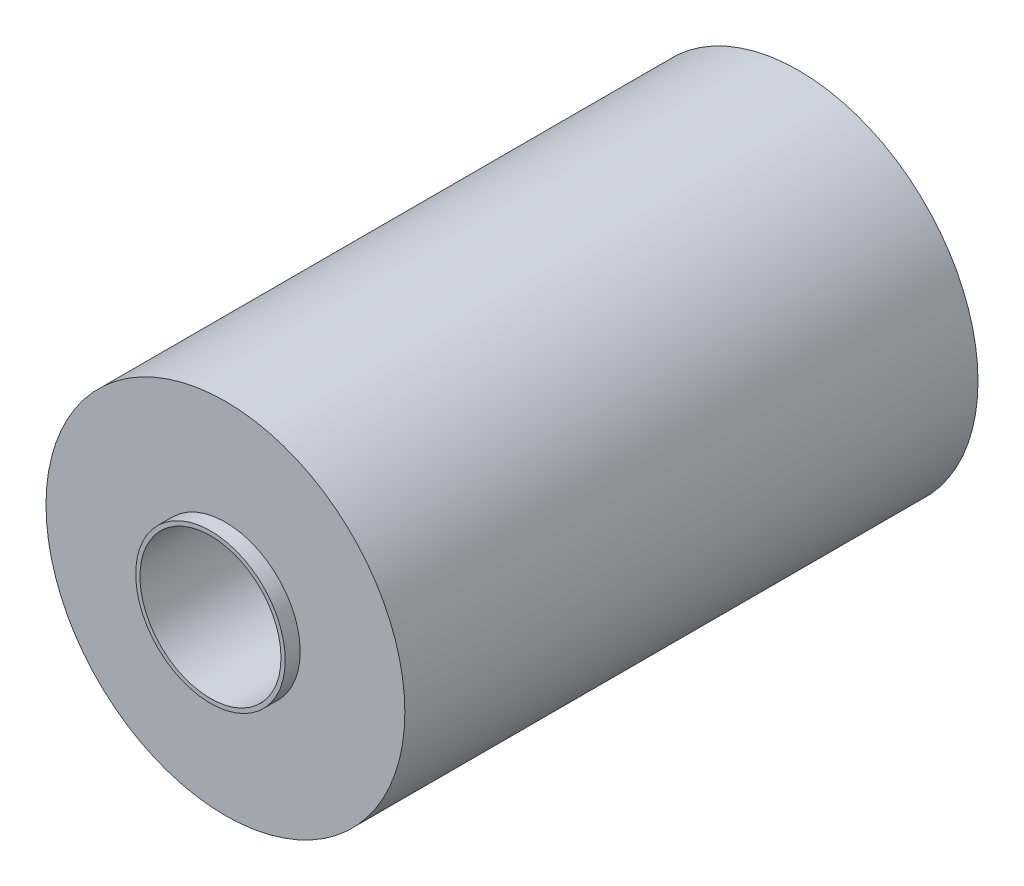
SolidWorks part; units mm, degrees
material "铜"
ref_plane "前视基准面" through (0, 0, 0) normal (0, 0, 1) x (1, 0, 0)
ref_plane "上视基准面" through (0, 0, 0) normal (0, 1, 0) x (1, 0, 0)
ref_plane "右视基准面" through (0, 0, 0) normal (1, 0, 0) x (0, 0, -1)
sketch "草图1" plane through (0, 0, 0) normal (0, 0, 1) x (1, 0, 0)
  circle A0 centre (0, 0) radius 36
  circle A1 centre (0, 0) radius 15
  dimension "D1" = 72
  dimension "D2" = 30
extrude "凸台-拉伸1" add sketch "草图1" along normal mid plane 115
sketch "草图2" plane through (0, 0, 0) normal (0, 0, 1) x (1, 0, 0)
  circle A0 centre (0, 0) radius 15 construction
  circle A1 centre (0, 0) radius 15
  circle A2 centre (0, 0) radius 14.15
  dimension "D1" = 28.3
extrude "凸台-拉伸2" add sketch "草图2" along normal offset from surface 3 and the other way up to surface (57.5 mm away) separate body up to face at (36, 0, 57.5) offset beyond the face yes other way up to face at (36, 0, -57.5)
